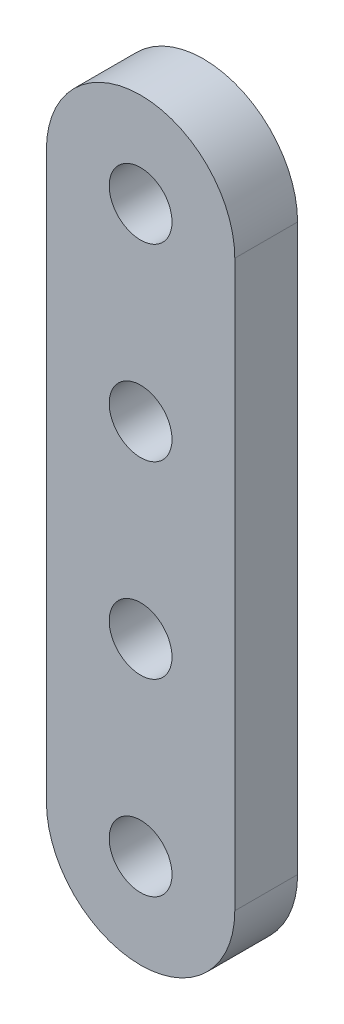
SolidWorks part; units mm, degrees
ref_plane "Alzado" through (0, 0, 0) normal (0, 0, 1) x (1, 0, 0)
ref_plane "Planta" through (0, 0, 0) normal (0, 1, 0) x (1, 0, 0)
ref_plane "Vista lateral" through (0, 0, 0) normal (1, 0, 0) x (0, 0, -1)
sketch "Model" plane through (0, 0, 0) normal (0, 0, 1) x (1, 0, 0)
  line L0 (213.2508, 152.4285) -> (213.2508, 179.4285)
  line L1 (204.2508, 179.4285) -> (204.2508, 152.4285)
  circle A0 centre (208.7508, 152.4285) radius 1.5
  circle A1 centre (208.7508, 161.4285) radius 1.5
  circle A2 centre (208.7508, 170.4285) radius 1.5
  arc A3 (204.2508, 152.4285) -> (213.2508, 152.4285) centre (208.7508, 152.4285) ccw
  arc A4 (213.2508, 179.4285) -> (204.2508, 179.4285) centre (208.7508, 179.4285) ccw
  circle A5 centre (208.7508, 179.4285) radius 1.5
extrude "Saliente-Extruir1" add sketch "Model" along normal blind 3
